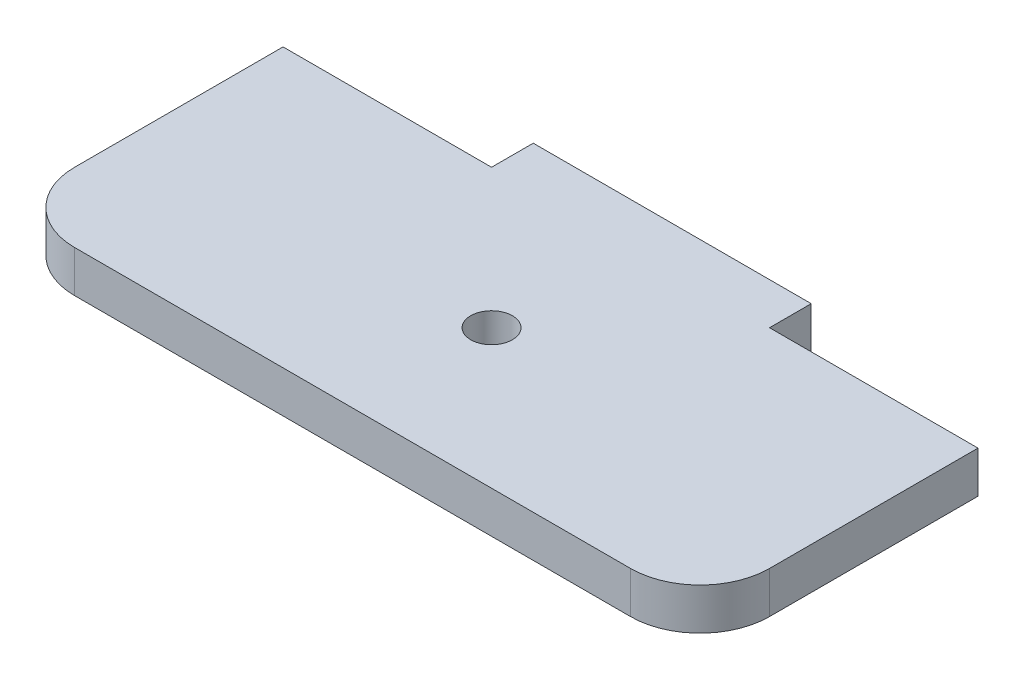
SolidWorks part; units mm, degrees
ref_plane "Alzado" through (0, 0, 0) normal (0, 0, 1) x (1, 0, 0)
ref_plane "Planta" through (0, 0, 0) normal (0, 1, 0) x (1, 0, 0)
ref_plane "Vista lateral" through (0, 0, 0) normal (1, 0, 0) x (0, 0, -1)
sketch "Croquis1" plane through (0, 0, 0) normal (0, 1, 0) x (1, 0, 0)
  line L1 (20, -10) -> (-20, -10)
  line L2 (25, -5) -> (25, 10)
  line L3 (25, 10) -> (-25, 10)
  line L4 (-25, -5) -> (-25, 10)
  line L5 (25, -10) -> (-25, 10) construction
  line L6 (25, 10) -> (-25, -10) construction
  circle A0 centre (0, 0) radius 1.5
  arc A1 (20, -10) -> (25, -5) centre (20, -5) ccw
  arc A2 (-20, -10) -> (-25, -5) centre (-20, -5) cw
  point P0 (0, 0)
  dimension "D3" = 3
  dimension "D4" = 5
  dimension "D1" = 50
  dimension "D2" = 20
extrude "Saliente-Extruir1" add sketch "Croquis1" along normal blind 3
sketch "Croquis2" plane through (0, 0, -10) normal (0, 0, -1) x (-1, 0, 0)
  line L0 (0, 0) -> (0, 3) construction
  line L1 (-25, 3) -> (25, 3) construction
  line L2 (-10, 3.125) -> (-10, -0.125) construction
  line L3 (10, 0) -> (-10, 0)
  line L4 (10, 0) -> (10, 3)
  line L5 (10, 3) -> (-10, 3)
  line L6 (-10, 0) -> (-10, 3)
  line L7 (10, 0) -> (-10, 3) construction
  line L8 (10, 3) -> (-10, 0) construction
  line L9 (10, -0.125) -> (10, 3.125) construction
  point P5 (0, 1.5)
  point P12 (10, 3)
extrude "Saliente-Extruir2" add sketch "Croquis2" along normal blind 3
